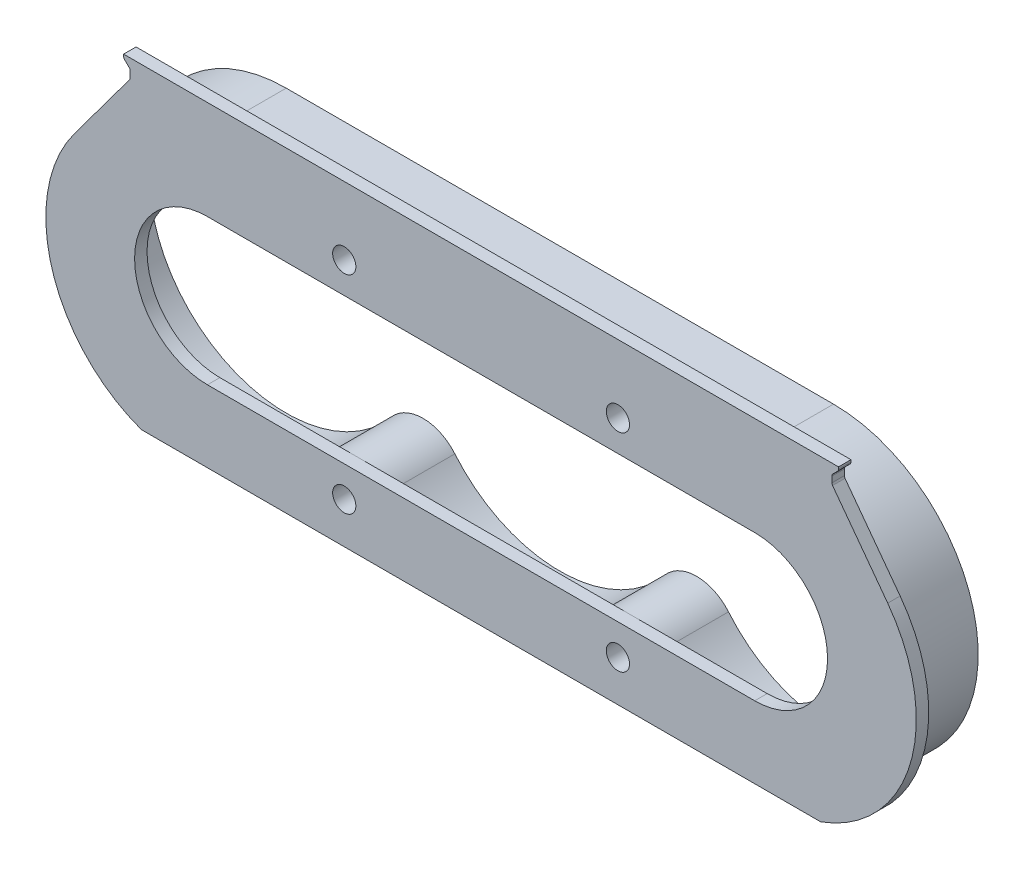
SolidWorks part; units mm, degrees
ref_plane "Front Plane" through (0, 0, 0) normal (0, 0, 1) x (1, 0, 0)
ref_plane "Top Plane" through (0, 0, 0) normal (0, 1, 0) x (1, 0, 0)
ref_plane "Right Plane" through (0, 0, 0) normal (1, 0, 0) x (0, 0, -1)
sketch "Sketch1" plane through (0, 0, 0) normal (0, 0, 1) x (1, 0, 0)
  line L2 (32.7948, -0.95) -> (98.7948, -0.95)
  line L3 (98.7948, 33.95) -> (32.7948, 33.95)
  line L4 (32.7948, -0.95) -> (98.7948, -0.95)
  line L5 (98.7948, 33.95) -> (32.7948, 33.95)
  circle A0 centre (49.2948, 29) radius 1.2 construction
  circle A1 centre (82.2948, 4) radius 1.2 construction
  arc A2 (32.7948, 33.95) -> (32.7948, -0.95) centre (32.7948, 16.5) ccw
  arc A3 (98.7948, -0.95) -> (98.7948, 33.95) centre (98.7948, 16.5) ccw
  arc A4 (32.7948, 33.95) -> (32.7948, -0.95) centre (32.7948, 16.5) ccw
  arc A5 (98.7948, -0.95) -> (98.7948, 33.95) centre (98.7948, 16.5) ccw
  circle A6 centre (49.2948, 4) radius 1.2 construction
  circle A7 centre (82.2948, 29) radius 1.2 construction
  circle A8 centre (82.2948, 29) radius 1.2
  circle A9 centre (49.2948, 4) radius 1.2
  circle A10 centre (82.2948, 4) radius 1.2
  circle A11 centre (49.2948, 29) radius 1.2
  arc A12 (45.4576, 27.0785) -> (45.4576, 5.9215) centre (32.7948, 16.5) ccw construction
  arc A13 (45.4576, 27.0785) -> (53.132, 27.0785) centre (49.2948, 30.284) ccw construction
  arc A14 (78.4576, 27.0785) -> (53.132, 27.0785) centre (65.7948, 16.5) ccw construction
  arc A15 (53.132, 5.9215) -> (45.4576, 5.9215) centre (49.2948, 2.716) ccw construction
  arc A16 (53.132, 5.9215) -> (78.4576, 5.9215) centre (65.7948, 16.5) ccw construction
  arc A17 (78.4576, 27.0785) -> (86.132, 27.0785) centre (82.2948, 30.284) ccw construction
  arc A18 (86.132, 5.9215) -> (86.132, 27.0785) centre (98.7948, 16.5) ccw construction
  arc A19 (86.132, 5.9215) -> (78.4576, 5.9215) centre (82.2948, 2.716) ccw construction
  arc A20 (86.132, 5.9215) -> (78.4576, 5.9215) centre (82.2948, 2.716) ccw
  arc A21 (86.132, 5.9215) -> (86.132, 27.0785) centre (98.7948, 16.5) ccw
  arc A22 (78.4576, 27.0785) -> (86.132, 27.0785) centre (82.2948, 30.284) ccw
  arc A23 (53.132, 5.9215) -> (78.4576, 5.9215) centre (65.7948, 16.5) ccw
  arc A24 (53.132, 5.9215) -> (45.4576, 5.9215) centre (49.2948, 2.716) ccw
  arc A25 (78.4576, 27.0785) -> (53.132, 27.0785) centre (65.7948, 16.5) ccw
  arc A26 (45.4576, 27.0785) -> (53.132, 27.0785) centre (49.2948, 30.284) ccw
  arc A27 (45.4576, 27.0785) -> (45.4576, 5.9215) centre (32.7948, 16.5) ccw
  dimension "D1" = 0
extrude "Boss-Extrude1" add sketch "Sketch1" along normal blind 8
sketch "Sketch2" plane through (0, 0, 8) normal (0, 0, 1) x (1, 0, 0)
  line L4 (30.8073, -2) -> (100.7824, -2)
  line L5 (114.8347, 25.9299) -> (108.1815, 34.8938)
  line L6 (108.1027, 35.1322) -> (108.1027, 35.8343)
  line L7 (23.4081, 34.8938) -> (16.7549, 25.9299)
  line L8 (30.8073, -2) -> (100.7824, -2)
  line L9 (114.8347, 25.9299) -> (108.1815, 34.8938)
  line L11 (23.4081, 34.8938) -> (16.7549, 25.9299)
  line L28 (108.1027, 35.1322) -> (108.1027, 35.8343)
  line L29 (108.2199, 36.1172) -> (108.7855, 36.6828)
  line L30 (108.2199, 36.1172) -> (108.7855, 36.6828)
  line L31 (108.9027, 36.9657) -> (108.9027, 37.2)
  line L32 (108.9027, 36.9657) -> (108.9027, 37.2)
  line L33 (108.9027, 37.2) -> (22.687, 37.2)
  line L34 (108.9027, 37.2) -> (22.687, 37.2)
  line L35 (22.687, 37.2) -> (22.687, 36.9657)
  line L36 (22.687, 37.2) -> (22.687, 36.9657)
  line L37 (22.8041, 36.6828) -> (23.3698, 36.1172)
  line L38 (22.8041, 36.6828) -> (23.3698, 36.1172)
  line L39 (23.487, 35.8343) -> (23.487, 35.1322)
  line L40 (23.487, 35.8343) -> (23.487, 35.1322)
  arc A2 (100.7824, -2) -> (114.8347, 25.9299) centre (100.7824, 15.5) ccw
  arc A3 (16.7549, 25.9299) -> (30.8073, -2) centre (30.8073, 15.5) ccw
  arc A4 (100.7824, -2) -> (114.8347, 25.9299) centre (100.7824, 15.5) ccw
  arc A5 (16.7549, 25.9299) -> (30.8073, -2) centre (30.8073, 15.5) ccw
  arc A24 (22.687, 36.9657) -> (22.8041, 36.6828) centre (23.087, 36.9657) ccw
  arc A25 (22.687, 36.9657) -> (22.8041, 36.6828) centre (23.087, 36.9657) ccw
  arc A26 (23.487, 35.8343) -> (23.3698, 36.1172) centre (23.087, 35.8343) ccw
  arc A27 (23.487, 35.8343) -> (23.3698, 36.1172) centre (23.087, 35.8343) ccw
  arc A28 (23.4081, 34.8938) -> (23.487, 35.1322) centre (23.087, 35.1322) ccw
  arc A29 (23.4081, 34.8938) -> (23.487, 35.1322) centre (23.087, 35.1322) ccw
  arc A30 (108.1027, 35.1322) -> (108.1815, 34.8938) centre (108.5027, 35.1322) ccw
  arc A31 (108.1027, 35.1322) -> (108.1815, 34.8938) centre (108.5027, 35.1322) ccw
  arc A32 (108.2199, 36.1172) -> (108.1027, 35.8343) centre (108.5027, 35.8343) ccw
  arc A33 (108.2199, 36.1172) -> (108.1027, 35.8343) centre (108.5027, 35.8343) ccw
  arc A34 (108.7855, 36.6828) -> (108.9027, 36.9657) centre (108.5027, 36.9657) ccw
  arc A35 (108.7855, 36.6828) -> (108.9027, 36.9657) centre (108.5027, 36.9657) ccw
  dimension "D1" = 0
extrude "Boss-Extrude2" add sketch "Sketch2" along normal blind 1.5
sketch "Sketch3" plane through (0, 0, 8) normal (0, 0, -1) x (-1, 0, 0)
  circle A0 centre (-49.2948, 4) radius 1.2 construction
  circle A1 centre (-49.2948, 29) radius 1.2 construction
  circle A2 centre (-82.2948, 4) radius 1.2 construction
  circle A3 centre (-82.2948, 29) radius 1.2 construction
  circle A4 centre (-49.2948, 4) radius 1.2
  circle A5 centre (-49.2948, 29) radius 1.2
  circle A6 centre (-82.2948, 4) radius 1.2
  circle A7 centre (-82.2948, 29) radius 1.2
  circle A8 centre (-49.2948, 29) radius 1.4
  circle A9 centre (-49.2948, 4) radius 1.4
  circle A10 centre (-82.2948, 4) radius 1.4
  circle A11 centre (-82.2948, 29) radius 1.4
  dimension "D1" = 0.2
  dimension "D2" = 0.2
extrude "Cut-Extrude1" cut sketch "Sketch3" against normal through all both and the other way through all contours A8 | A9 | A10 | A11
sketch "Sketch4" plane through (0, 0, 8) normal (0, 0, -1) x (-1, 0, 0)
  line L0 (-98.7948, 16.5) -> (-32.7948, 16.5) construction
  line L1 (-98.7948, 25.284) -> (-32.7948, 25.284)
  line L2 (-98.7948, 7.716) -> (-32.7948, 7.716)
  arc A0 (-98.7948, 25.284) -> (-98.7948, 7.716) centre (-98.7948, 16.5) ccw
  arc A1 (-32.7948, 7.716) -> (-32.7948, 25.284) centre (-32.7948, 16.5) ccw
  arc A2 (-78.4576, 5.9215) -> (-86.132, 5.9215) centre (-82.2948, 2.716) ccw construction
  point P4 (-65.7948, 16.5)
extrude "Cut-Extrude2" cut sketch "Sketch4" against normal through all
sketch "Sketch5" plane through (0, 0, 8) normal (0, 0, -1) x (-1, 0, 0)
  line L0 (-32.7948, -0.95) -> (-98.7948, -0.95) construction
  line L1 (-12.434, -6.9663) -> (-129.7059, -6.9663)
  line L2 (-12.434, -6.9663) -> (-12.434, -0.95)
  line L3 (-12.434, -0.95) -> (-129.7059, -0.95)
  line L4 (-129.7059, -6.9663) -> (-129.7059, -0.95)
extrude "Cut-Extrude3" cut sketch "Sketch5" against normal through all
